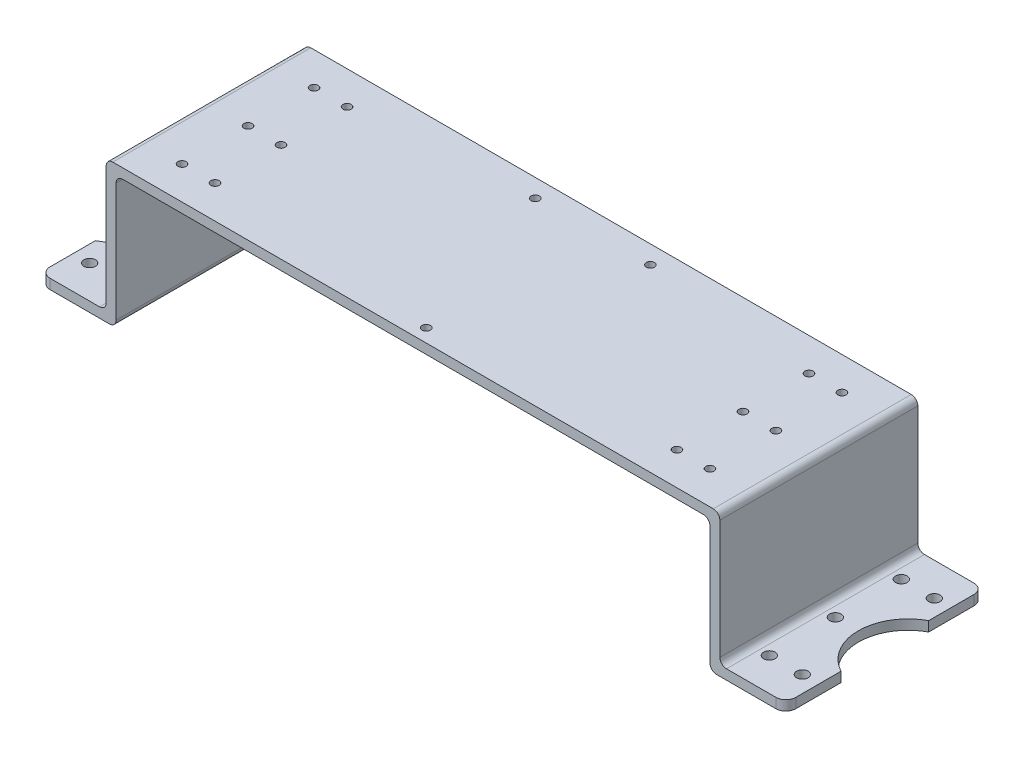
SolidWorks part; units mm, degrees
ref_plane "Front" through (0, 0, 0) normal (0, 0, 1) x (1, 0, 0)
ref_plane "Top" through (0, 0, 0) normal (0, 1, 0) x (1, 0, 0)
ref_plane "Right" through (0, 0, 0) normal (1, 0, 0) x (0, 0, -1)
sketch "草图1" plane through (0, 0, 0) normal (0, 1, 0) x (1, 0, 0)
  line L1 (-93, 30) -> (93, 30)
  line L2 (-93, 30) -> (-93, -30)
  line L3 (-93, -30) -> (93, -30)
  line L4 (93, 30) -> (93, -30)
  line L5 (-93, 30) -> (93, -30) construction
  line L6 (-93, -30) -> (93, 30) construction
  point P0 (0, 0)
  dimension "D1" = 186
  dimension "D2" = 60
extrude "凸台-拉伸1" add sketch "草图1" along normal blind 3 contours L3 L4 L1 L2
sketch "草图2" plane through (0, 0, 0) normal (0, -1, 0) x (1, 0, 0)
  line L0 (-93, -30) -> (93, -30) construction
  line L1 (-93, 30) -> (-90, 30)
  line L2 (-93, 30) -> (-93, -30)
  line L3 (-93, -30) -> (-90, -30)
  line L4 (-90, 30) -> (-90, -30)
  dimension "D1" = 3
extrude "凸台-拉伸2" add sketch "草图2" along normal blind 40
sketch "草图3" plane through (-93, 0, 0) normal (-1, 0, 0) x (0, 0, 1)
  line L0 (30, 3) -> (30, -40) construction
  line L1 (-30, -40) -> (30, -40)
  line L2 (-30, -40) -> (-30, -37)
  line L3 (-30, -37) -> (30, -37)
  line L4 (30, -40) -> (30, -37)
  dimension "D1" = 3
extrude "凸台-拉伸3" add sketch "草图3" along normal blind 20 contours L3 L4 L1 L2
sketch "草图4" plane through (0, -37, 0) normal (0, 1, 0) x (1, 0, 0)
  line L0 (0, -65.2575) -> (0, 64.6093) construction
  line L1 (-113, -30) -> (-93, -30) construction
  circle A0 centre (-98, -20) radius 1.75
  dimension "D1" = 98
  dimension "D3" = 3.5
  dimension "D2" = 10
extrude "切除-拉伸1" cut sketch "草图4" against normal through all
pattern_linear "阵列(线性)1" count 3 spacing 20 along (0, 0, -1) count 2 spacing 10 along (-1, 0, 0) of "切除-拉伸1"
mirror "镜向4" about plane through (0, 0, 0) normal (1, 0, 0) of "阵列(线性)1", "凸台-拉伸3", "凸台-拉伸2", "切除-拉伸1"
sketch "草图5" plane through (0, 3, 0) normal (0, 1, 0) x (1, 0, 0)
  line L0 (-93, -30) -> (93, -30) construction
  circle A0 centre (0, -26) radius 1
  dimension "D1" = 2
  dimension "D2" = 4
extrude "切除-拉伸2" cut sketch "草图5" against normal blind 3
sketch "草图6" plane through (0, 3, 0) normal (0, 1, 0) x (1, 0, 0)
  circle A0 centre (-17.45, 24.5) radius 1
  circle A1 centre (0, -26) radius 1 construction
  dimension "D1" = 2
  dimension "D2" = 50.5
  dimension "D3" = 17.45
extrude "切除-拉伸3" cut sketch "草图6" against normal blind 3 contours A0
mirror "镜向5" about plane through (0, 0, 0) normal (1, 0, 0) of "切除-拉伸3"
sketch "草图7" plane through (0, 3, 0) normal (0, 1, 0) x (1, 0, 0)
  line L0 (-93, -30) -> (93, -30) construction
  line L1 (0, -50) -> (0, 50) construction
  circle A0 centre (-70, -20) radius 1
  dimension "D1" = 2
  dimension "D2" = 10
  dimension "D3" = 70
extrude "切除-拉伸4" cut sketch "草图7" against normal blind 3
pattern_linear "阵列(线性)2" count 3 spacing 20 along (0, 0, -1) count 2 spacing 10 along (-1, 0, 0) of "切除-拉伸4"
mirror "镜向6" about plane through (0, 0, 0) normal (1, 0, 0) of "阵列(线性)2", "切除-拉伸4"
hole_wizard "M3 螺纹孔1" positions "草图8" profile "草图9" tap size "M3" standard "GB" end condition through all
sketch "草图8" plane through (0, 3, 0) normal (0, 1, 0) x (1, 0, 0)
  point P0 (-80, -20)
  point P3 (-70, -20)
  point P6 (-70, 0)
  point P9 (-80, 0)
  point P12 (-70, 20)
  point P15 (-80, 20)
  point P18 (70, -20)
  point P21 (80, -20)
  point P24 (70, 0)
  point P27 (80, 0)
  point P30 (70, 20)
  point P33 (80, 20)
sketch "草图9" plane through (-80, 3, 20) normal (1, 0, 0) x (0, 0, 1)
  line L0 (0, 0) -> (0, 43)
  line L1 (0, 43) -> (1.25, 43)
  line L2 (1.25, 43) -> (1.25, 0)
  line L5 (1.25, 0) -> (0, 0)
  line L11 (0, -6.35) -> (0, 107.95) construction
  dimension "通孔螺纹孔钻头直径" = 2.5
  dimension "通孔螺纹孔钻头深度" = 43
cosmetic thread "孔螺蚊线1" parameters "D2"=3
cosmetic thread "孔螺蚊线2" parameters "D2"=3
cosmetic thread "孔螺蚊线3" parameters "D2"=3
cosmetic thread "孔螺蚊线4" parameters "D2"=3
cosmetic thread "孔螺蚊线5" parameters "D2"=3
cosmetic thread "孔螺蚊线6" parameters "D2"=3
cosmetic thread "孔螺蚊线7" parameters "D2"=3
cosmetic thread "孔螺蚊线8" parameters "D2"=3
cosmetic thread "孔螺蚊线9" parameters "D2"=3
cosmetic thread "孔螺蚊线10" parameters "D2"=3
cosmetic thread "孔螺蚊线11" parameters "D2"=3
cosmetic thread "孔螺蚊线12" parameters "D2"=3
hole_wizard "M3 螺纹孔2" positions "草图10" profile "草图11" tap size "M3" standard "GB" end condition through all
sketch "草图10" plane through (0, 3, 0) normal (0, 1, 0) x (1, 0, 0)
  point P0 (-17.45, 24.5)
  point P3 (17.45, 24.5)
  point P6 (0, -26)
sketch "草图11" plane through (-17.45, 3, -24.5) normal (1, 0, 0) x (0, 0, 1)
  line L0 (0, 0) -> (0, 43)
  line L1 (0, 43) -> (1.25, 43)
  line L2 (1.25, 43) -> (1.25, 0)
  line L5 (1.25, 0) -> (0, 0)
  line L11 (0, -6.35) -> (0, 107.95) construction
  dimension "通孔螺纹孔钻头直径" = 2.5
  dimension "通孔螺纹孔钻头深度" = 43
cosmetic thread "孔螺蚊线13" parameters "D2"=3
cosmetic thread "孔螺蚊线14" parameters "D2"=3
cosmetic thread "孔螺蚊线15" parameters "D2"=3
sketch "草图12" plane through (0, -37, 0) normal (0, 1, 0) x (1, 0, 0)
  line L0 (-108, 0) -> (-120, 0) construction
  circle A0 centre (-120, 0) radius 15
  point P3 (-121.0866, 0)
  point P6 (-113, 0)
  dimension "D1" = 30
  dimension "D2" = 12
extrude "切除-拉伸5" cut sketch "草图12" against normal through all
mirror "镜向7" about plane through (0, 0, 0) normal (1, 0, 0) of "切除-拉伸5"
fillet "圆角2" radius 2 2 edges at (-90, 0, 0) (-93, 3, 0)
fillet "圆角3" radius 2 2 edges at (90, 0, 0) (93, 3, 0)
fillet "圆角4" radius 2 4 edges at (-90, -40, 0) (-93, -37, 0) (93, -37, 0) (90, -40, 0)
fillet "圆角5" radius 3 4 edges at (-113, -38.5, 30) (-113, -38.5, -30) (113, -38.5, -30) (113, -38.5, 30)
